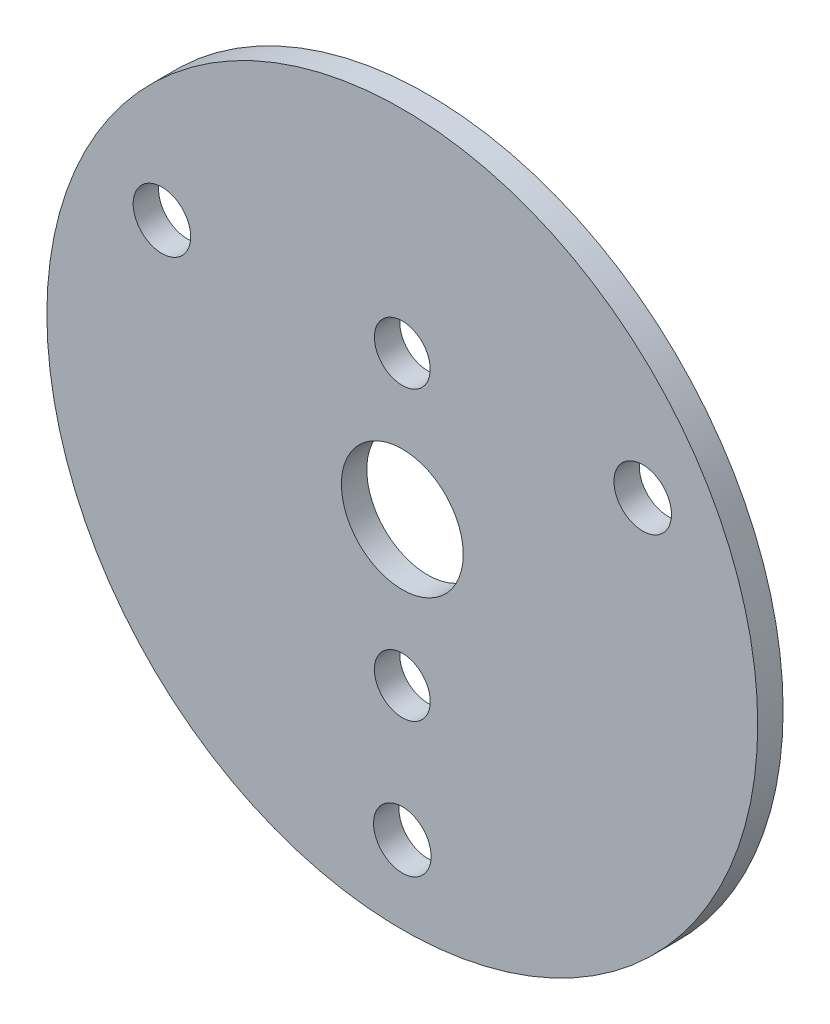
SolidWorks part; units mm, degrees
ref_plane "Front Plane" through (0, 0, 0) normal (0, 0, 1) x (1, 0, 0)
ref_plane "Top Plane" through (0, 0, 0) normal (0, 1, 0) x (1, 0, 0)
ref_plane "Right Plane" through (0, 0, 0) normal (1, 0, 0) x (0, 0, -1)
sketch "S01 - Flat 1.5 mm steel disc and gearbox pilot" plane through (0, 0, 0) normal (0, 0, 1) x (1, 0, 0)
  circle A0 centre (0, 0) radius 21
  circle A1 centre (0, 0) radius 3.6
  dimension "D1" = 7.2
  dimension "D2" = 42
extrude "01 - Flat 1.5 mm steel disc and gearbox pilot" add sketch "S01 - Flat 1.5 mm steel disc and gearbox pilot" along normal blind 1.5
sketch "S02 - Three carrier bolts" plane through (0, 0, 0) normal (0, 0, 1) x (1, 0, 0)
  circle A0 centre (14.2028, 8.2) radius 1.7
  circle A1 centre (-14.2028, 8.2) radius 1.7
  circle A2 centre (0, -16.4) radius 1.7
  dimension "D1" = 3.4
  dimension "D2" = 3.4
  dimension "D3" = 3.4
  dimension "D4" = 14.2028
  dimension "D5" = 14.2028
  dimension "D6" = 8.2
  dimension "D7" = 16.4
extrude "02 - Three carrier bolts" cut sketch "S02 - Three carrier bolts" along normal blind 1.7 from offset 0.1 offset against normal yes
sketch "S03 - Two Pololu face screws at 17 mm pitch" plane through (0, 0, 0) normal (0, 0, 1) x (1, 0, 0)
  circle A0 centre (0, 8.5) radius 1.65
  circle A1 centre (0, -8.5) radius 1.65
  dimension "D1" = 3.3
  dimension "D2" = 3.3
  dimension "D3" = 8.5
  dimension "D4" = 8.5
extrude "03 - Two Pololu face screws at 17 mm pitch" cut sketch "S03 - Two Pololu face screws at 17 mm pitch" along normal blind 1.7 from offset 0.1
